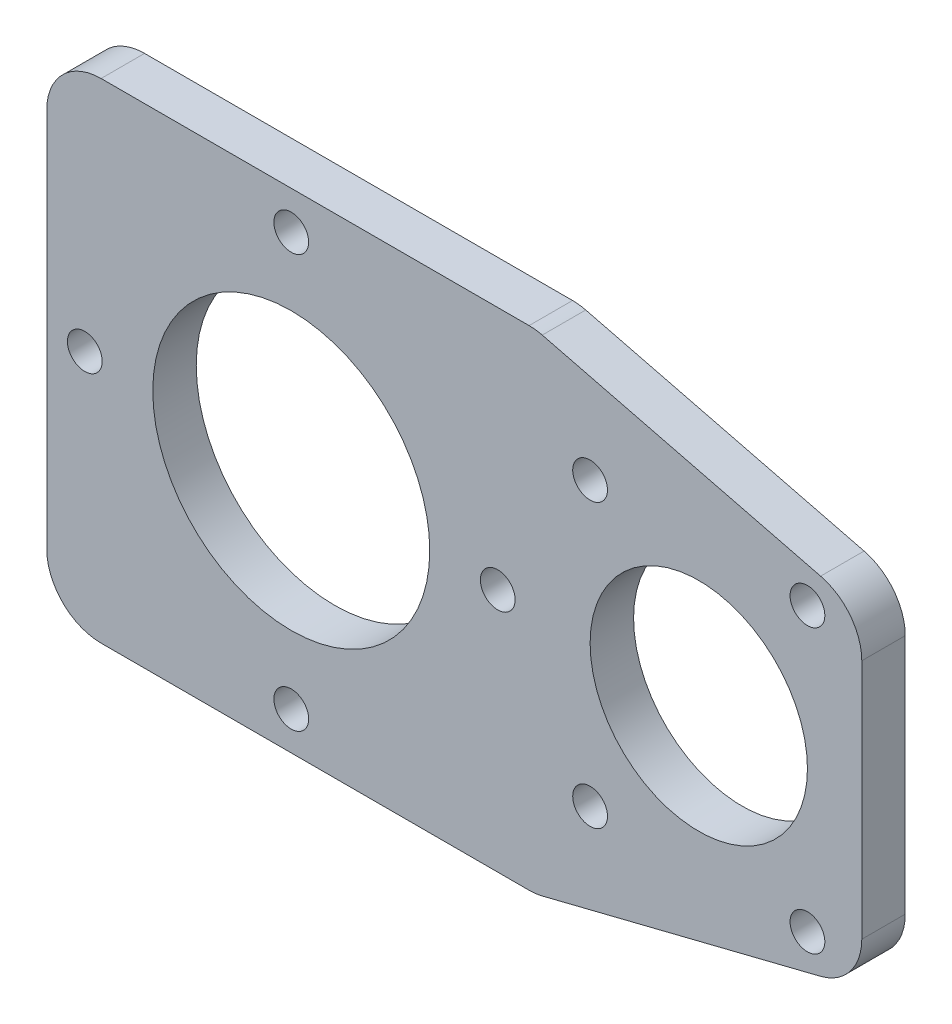
SolidWorks part; units mm, degrees
ref_plane "前视基准面" through (0, 0, 0) normal (0, 0, 1) x (1, 0, 0)
ref_plane "上视基准面" through (0, 0, 0) normal (0, 1, 0) x (1, 0, 0)
ref_plane "右视基准面" through (0, 0, 0) normal (1, 0, 0) x (0, 0, -1)
other "Configuration Table"
sketch "草图1" plane through (0, 0, 0) normal (0, 0, 1) x (1, 0, 0)
  line L0 (-22.5, 0) -> (22.5, 0) construction
  line L1 (-22.5, 22.5) -> (22.5, 22.5)
  line L2 (-22.5, 22.5) -> (-22.5, -22.5)
  line L3 (-22.5, -22.5) -> (22.5, -22.5)
  line L4 (22.5, 22.5) -> (22.5, -22.5)
  line L5 (-22.5, 22.5) -> (22.5, -22.5) construction
  line L6 (-22.5, -22.5) -> (22.5, 22.5) construction
  line L7 (0, 0) -> (0, 8.2537) construction
  circle A0 centre (19, 0) radius 1.6
  circle A1 centre (-19, 0) radius 1.6
  point P0 (0, 0)
  dimension "D2" = 3.2
  dimension "D3" = 19
  dimension "D1" = 45
extrude "凸台-拉伸1" add sketch "草图1" along normal blind 4
sketch "草图2" plane through (0, 0, 4) normal (0, 0, 1) x (1, 0, 0)
  line L0 (0, 0) -> (77.638, 0) construction
  line L1 (22.5, 22.5) -> (52.5, 15)
  line L2 (52.5, 15) -> (52.5, -15)
  line L3 (52.5, 0) -> (22.5, 0)
  line L4 (22.5, -22.5) -> (22.5, 22.5) construction
  line L5 (22.5, -22.5) -> (22.5, 22.5)
  line L6 (22.5, -22.5) -> (52.5, -15)
  line M6 (22.5, -22.5) -> (22.5, 22.5)
  dimension "D1" = 15
  dimension "D2" = 30
extrude "凸台-拉伸2" add sketch "草图2" against normal blind 4 contours L3 L2 L1 M6 | L6 L2 L3 M6
sketch "草图3" plane through (0, 0, 4) normal (0, 0, 1) x (1, 0, 0)
  line L0 (22.5, 22.5) -> (22.5, -22.5) construction
  line L1 (22.5, 13) -> (52.5425, 13) construction
  line L3 (22.5, 0) -> (52.5, 0) construction
  line L4 (52.5, 15) -> (52.5, -15) construction
  line L5 (22.5, -13) -> (52.5425, -13) construction
  circle A0 centre (27.5, 13) radius 1.6
  circle A1 centre (47.5, 13) radius 1.6
  circle A2 centre (47.5, -13) radius 1.6
  circle A3 centre (27.5, -13) radius 1.6
  dimension "D2" = 3.2
  dimension "D3" = 5
  dimension "D4" = 20
  dimension "D5" = 3.2
  dimension "D1" = 13
extrude "切除-拉伸1" cut sketch "草图3" against normal blind 4
fillet "圆角1" radius 5 3 edges at (52.5, -15, 2) (52.5, 15, 2) (22.5, 22.5, 2)
sketch "草图4" plane through (0, 0, 4) normal (0, 0, 1) x (1, 0, 0)
  line L0 (0, -19) -> (0, 19) construction
  line L3 (0, 0) -> (9.966, 0) construction
  circle A0 centre (0, 19) radius 1.6
  circle A1 centre (0, -19) radius 1.6
  dimension "D1" = 3.2
  dimension "D2" = 19
extrude "切除-拉伸2" cut sketch "草图4" against normal blind 4
sketch "草图5" plane through (0, 0, 4) normal (0, 0, 1) x (1, 0, 0)
  line L0 (27.5, 13) -> (47.5, -13) construction
  circle A4 centre (0, 0) radius 12.7442
  circle A5 centre (37.5, 0) radius 10
  dimension "D1" = 20
  dimension "D3" = 25.4884
extrude "切除-拉伸3" cut sketch "草图5" against normal blind 10 contours A4 | A5
fillet "圆角2" radius 5 2 edges at (-22.5, -22.5, 2) (-22.5, 22.5, 2)
fillet "圆角3" radius 5 1 edges at (22.5, -22.5, 2)
